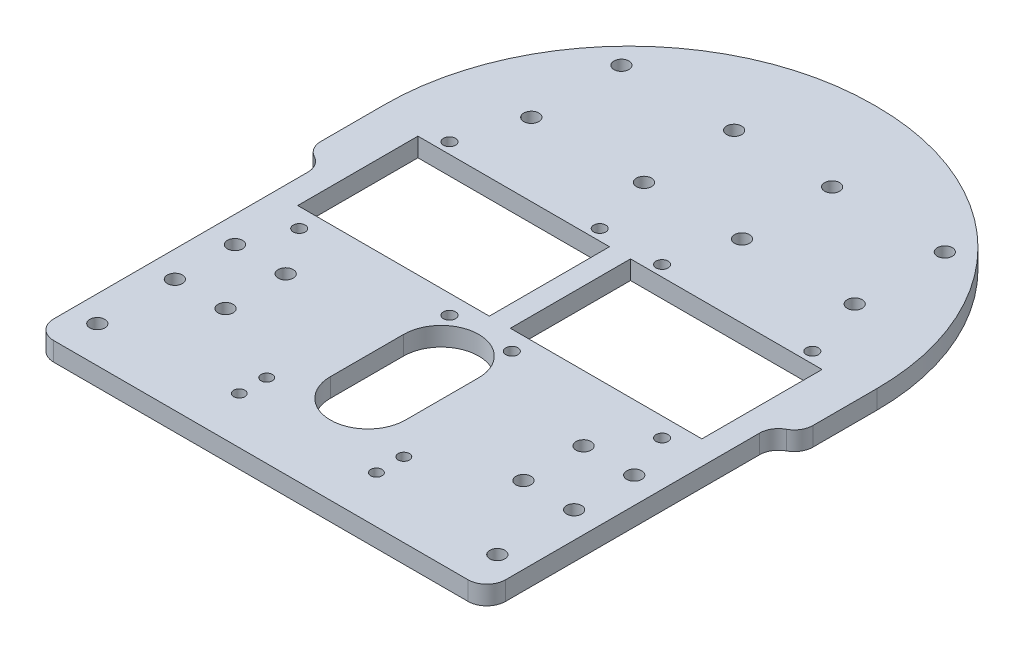
SolidWorks part; units mm, degrees
ref_plane "Front Plane" through (0, 0, 0) normal (0, 0, 1) x (1, 0, 0)
ref_plane "Top Plane" through (0, 0, 0) normal (0, 1, 0) x (1, 0, 0)
ref_plane "Right Plane" through (0, 0, 0) normal (1, 0, 0) x (0, 0, -1)
sketch "Sketch1" plane through (0, 0, 0) normal (0, 1, 0) x (1, 0, 0)
  line L0 (0, 90.99) -> (0, -94.01) construction
  line L1 (-94.5795, 0) -> (90.4205, 0) construction
  line L2 (-65.5, 80) -> (-65.5, -83.5)
  line L3 (-65.5, -83.5) -> (65.5, -83.5)
  line L4 (65.5, -83.5) -> (65.5, 80)
  line L5 (65.5, 80) -> (-65.5, 80)
  line L6 (-65.5, -7) -> (-65.5, -83.5)
  line L7 (-65.5, -83.5) -> (-60.15, -83.5)
  line L8 (-60.15, -83.5) -> (-60.15, -7)
  line L9 (-60.15, -7) -> (-65.5, -7)
  line L10 (60.15, -83.5) -> (60.15, -7)
  line L11 (65.5, -83.5) -> (60.15, -83.5)
  line L12 (65.5, -7) -> (65.5, -83.5)
  line L13 (60.15, -7) -> (65.5, -7)
  dimension "D1" = 60.15
  dimension "D2" = 65.5
  dimension "D3" = 80
  dimension "D4" = 185
  dimension "D5" = 185
  dimension "D7" = 76.5
  dimension "D8" = 87
  dimension "D9" = 65.5
extrude "Boss-Extrude2" add sketch "Sketch1" along normal blind 5 contours L10 L13 L4 L5 L2 L9 L8 L7 L3 L11
fillet "Fillet8" radius 65 2 edges at (65.5, 2.5, -80) (-65.5, 2.5, -80)
sketch "Sketch4" plane through (0, 5, 0) normal (0, 1, 0) x (1, 0, 0)
  line L0 (0, 0) -> (0, 80) construction
  line L1 (0, 80) -> (0, -83.5) construction
  line L2 (0, -35.5) -> (0, -55) construction
  line L3 (-65.5, 4) -> (65.5, 4) construction
  line L4 (-65.5, 15) -> (-65.5, -7) construction
  line L5 (65.5, -7) -> (65.5, 15) construction
  line L6 (-60.15, -83.5) -> (-60.15, -7) construction
  line L7 (0.5, 80) -> (-0.5, 80) construction
  line L8 (-60.15, -83.5) -> (60.15, -83.5) construction
  line L9 (60.15, -83.5) -> (60.15, -7) construction
  line L10 (-60.15, -45.25) -> (60.15, -45.25) construction
  line L13 (10, -35.5) -> (10, -55)
  line L16 (-10, -35.5) -> (-10, -55)
  line L17 (-53.7989, 12.1126) -> (-2.7989, 12.1126)
  line L18 (-2.7989, 12.1126) -> (-53.7989, 12.1126) construction
  line L19 (-53.7989, 12.1126) -> (-53.7989, -19.8874) construction
  line L20 (-2.7989, 12.1126) -> (-2.7989, -19.8874)
  line L21 (-2.7989, -19.8874) -> (-53.7989, -19.8874)
  line L22 (-53.7989, -19.8874) -> (-53.7989, 12.1126)
  line L23 (2.7989, -19.8874) -> (53.7989, -19.8874)
  line L24 (2.7989, 12.1126) -> (2.7989, -19.8874)
  line L25 (53.7989, 12.1126) -> (2.7989, 12.1126)
  line L26 (53.7989, -19.8874) -> (53.7989, 12.1126)
  line L27 (-60.15, -83.5) -> (-60.15, -7) construction
  line L28 (60.15, -83.5) -> (60.15, -7) construction
  line L29 (-60.15, -83.5) -> (60.15, -83.5) construction
  line L32 (-60.15, -83.5) -> (-60.15, -7) construction
  line L33 (-60.15, -83.5) -> (60.15, -83.5) construction
  circle A2 centre (-39.65, -37.25) radius 2
  circle A10 centre (39.65, -37.25) radius 2
  circle A13 centre (39.65, -53.25) radius 2
  circle A14 centre (-39.65, -53.25) radius 2
  circle A15 centre (-53.15, -37.25) radius 2
  circle A16 centre (-53.15, -53.25) radius 2
  circle A17 centre (53.15, -53.25) radius 2
  circle A18 centre (53.15, -37.25) radius 2
  arc A23 (10, -35.5) -> (-10, -35.5) centre (0, -35.5) ccw
  arc A24 (-10, -55) -> (10, -55) centre (0, -55) ccw
  circle A25 centre (-48.2989, 15.0126) radius 1.605
  circle A26 centre (-8.2989, 15.0126) radius 1.605
  circle A27 centre (-48.2989, -24.9874) radius 1.605
  circle A28 centre (-8.2989, -24.9874) radius 1.605
  circle A29 centre (48.2989, -24.9874) radius 1.605
  circle A30 centre (8.2989, -24.9874) radius 1.605
  circle A31 centre (8.2989, 15.0126) radius 1.605
  circle A32 centre (48.2989, 15.0126) radius 1.605
  circle A37 centre (13.0471, 55.5443) radius 2
  circle A38 centre (43.0471, 55.5443) radius 2
  circle A39 centre (43.0471, 31.5443) radius 2
  circle A40 centre (13.0471, 31.5443) radius 2
  circle A41 centre (-43.0471, 55.5443) radius 2
  circle A42 centre (-43.0471, 31.5443) radius 2
  circle A43 centre (-13.0471, 31.5443) radius 2
  circle A44 centre (-13.0471, 55.5443) radius 2
  circle A45 centre (-18.2487, -71) radius 1.5
  circle A51 centre (-53.249, -73.7963) radius 2
  circle A52 centre (53.249, -73.7963) radius 2
  circle A53 centre (18.2513, -71) radius 1.5
  circle A54 centre (-18.2487, -63.7) radius 1.5
  circle A55 centre (18.2513, -63.7) radius 1.5
  point P50 (0, -45.25)
  point P112 (0, 0)
  dimension "D2" = 4
  dimension "D13" = 4
  dimension "D10" = 7
  dimension "D11" = 20
  dimension "D5" = 3.21
  dimension "D6" = 4
  dimension "D7" = 3
  dimension "D18" = 12.5
  dimension "D8" = 3
  dimension "D22" = 3
  dimension "D23" = 3
  dimension "D3" = 16
  dimension "D4" = 16
  dimension "D9" = 13.5
  dimension "D12" = 41.9013
  dimension "D14" = 6.901
  dimension "D15" = 9.7037
  dimension "D16" = 19.5
  dimension "D17" = 41.8987
  dimension "D19" = 12.5
  dimension "D20" = 41.9013
  dimension "D21" = 41.8987
  dimension "D24" = 7.3
  dimension "D25" = 7.3
extrude "Cut-Extrude1" cut sketch "Sketch4" against normal blind 5
ref_plane "Plane1" through (60.15, 5, 7) normal (0, 0, -1) x (-1, 0, 0)
fillet "Fillet9" radius 5 4 edges at (65.5, 2.5, 7) (60.15, 2.5, 83.5) (-60.15, 2.5, 83.5) (-65.5, 2.5, 7)
fillet "Fillet10" radius 5 2 edges at (60.15, 2.5, 7) (-60.15, 2.5, 7)
